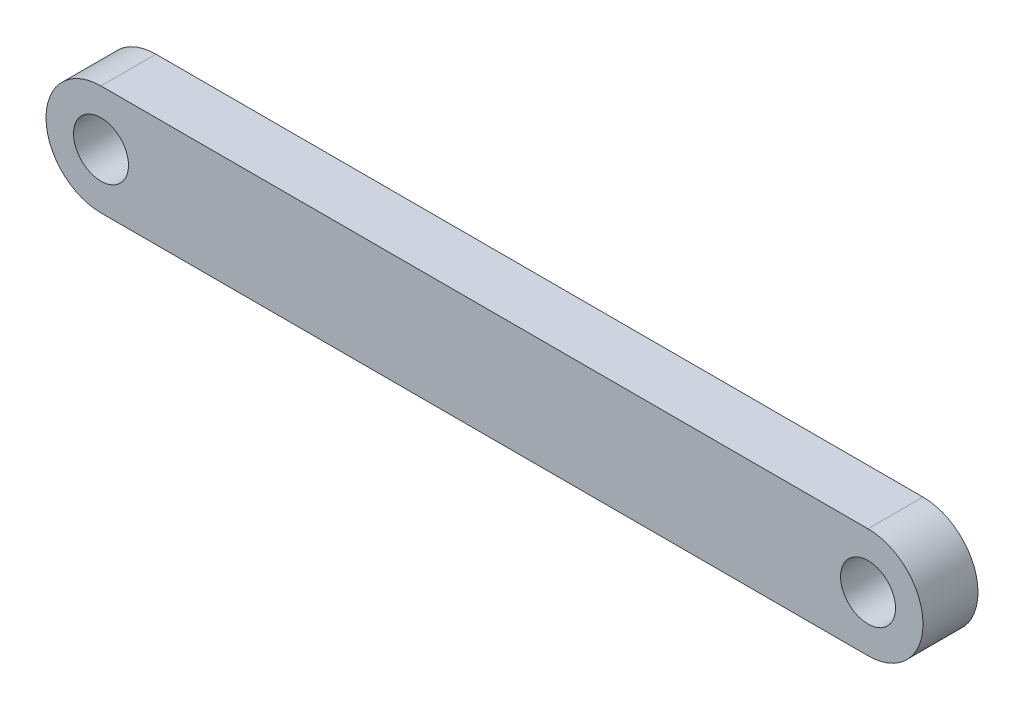
SolidWorks part; units mm, degrees
ref_plane "前基準面" through (0, 0, 0) normal (0, 0, 1) x (1, 0, 0)
ref_plane "上基準面" through (0, 0, 0) normal (0, 1, 0) x (1, 0, 0)
ref_plane "右基準面" through (0, 0, 0) normal (1, 0, 0) x (0, 0, -1)
sketch "草圖1" plane through (0, 0, 0) normal (0, 0, 1) x (1, 0, 0)
  line L0 (-13.95, 2.0007) -> (13.95, 2.0007)
  line L1 (-13.95, -1.9993) -> (13.95, -1.9993)
  arc A0 (-13.95, 2.0007) -> (-13.95, -1.9993) centre (-13.95, 0.0007) ccw
  arc A1 (13.95, -1.9993) -> (13.95, 2.0007) centre (13.95, 0.0007) ccw
  circle A2 centre (-13.95, 0.0007) radius 1
  circle A3 centre (13.95, 0.0007) radius 1
  dimension "D1" = 27.9
  dimension "D2" = 2
  dimension "D3" = 2
  dimension "D4" = 2
  dimension "D5" = 13.95
extrude "填料-伸長1" add sketch "草圖1" along normal blind 2
